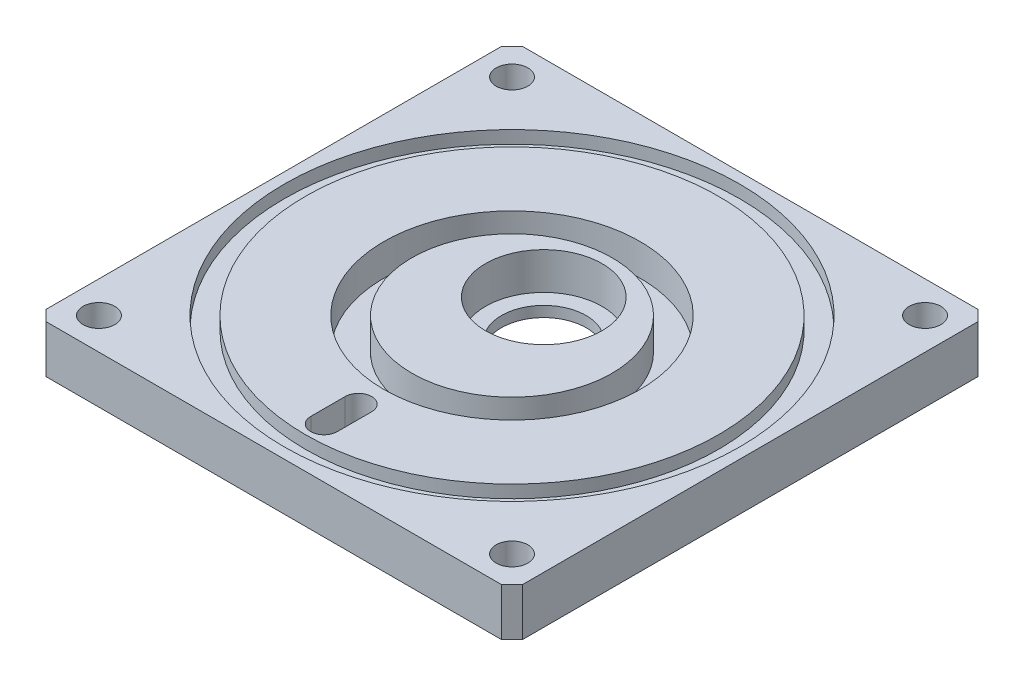
SolidWorks part; units mm, degrees
ref_plane "前视基准面" through (0, 0, 0) normal (0, 0, 1) x (1, 0, 0)
ref_plane "上视基准面" through (0, 0, 0) normal (0, 1, 0) x (1, 0, 0)
ref_plane "右视基准面" through (0, 0, 0) normal (1, 0, 0) x (0, 0, -1)
sketch "草图1" plane through (0, 0, 0) normal (0, 1, 0) x (1, 0, 0)
  line L1 (-22.5, -22.5) -> (22.5, -22.5)
  line L2 (-22.5, -22.5) -> (-22.5, 22.5)
  line L3 (-22.5, 22.5) -> (22.5, 22.5)
  line L4 (22.5, -22.5) -> (22.5, 22.5)
  line L5 (-22.5, -22.5) -> (22.5, 22.5) construction
  line L6 (-22.5, 22.5) -> (22.5, -22.5) construction
  point P0 (0, 0)
  dimension "D1" = 45
  dimension "D2" = 45
extrude "凸台-拉伸1" add sketch "草图1" along normal blind 4.5
sketch "草图2" plane through (0, 4.5, 0) normal (0, 1, 0) x (1, 0, 0)
  line L0 (0, 0) -> (0, 3) construction
  circle A0 centre (0, 3) radius 5.5
  dimension "D2" = 11
  dimension "D1" = 3
extrude "切除-拉伸1" cut sketch "草图2" against normal blind 3.5
sketch "草图3" plane through (0, 1, 0) normal (0, 1, 0) x (1, 0, 0)
  circle A0 centre (0, 3) radius 4
  dimension "D1" = 8
extrude "切除-拉伸2" cut sketch "草图3" against normal through all
sketch "草图4" plane through (0, 4.5, 0) normal (0, 1, 0) x (1, 0, 0)
  circle A0 centre (0, 0) radius 9.45
  circle A1 centre (0, 0) radius 12.1
  dimension "D1" = 18.9
  dimension "D2" = 24.2
extrude "切除-拉伸3" cut sketch "草图4" against normal blind 3
sketch "草图5" plane through (0, 4.5, 0) normal (0, 1, 0) x (1, 0, 0)
  circle A0 centre (0, 0) radius 19.5
  circle A1 centre (0, 0) radius 21.5
  dimension "D1" = 43
  dimension "D2" = 39
extrude "切除-拉伸4" cut sketch "草图5" against normal blind 1.2
sketch "草图6" plane through (0, 4.5, 0) normal (0, 1, 0) x (1, 0, 0)
  line L0 (0, -19) -> (0, -14.5) construction
  line L1 (0, -14.5) -> (0, -17.75) construction
  line L2 (1.25, -14.5) -> (1.25, -17.75)
  line L3 (-1.25, -14.5) -> (-1.25, -17.75)
  circle A0 centre (0, 0) radius 19 construction
  arc A1 (1.25, -14.5) -> (-1.25, -14.5) centre (0, -14.5) ccw
  arc A2 (-1.25, -17.75) -> (1.25, -17.75) centre (0, -17.75) ccw
  point P5 (0, -16.125)
  dimension "D1" = 38
  dimension "D2" = 4.5
  dimension "D3" = 1.25
extrude "切除-拉伸5" cut sketch "草图6" against normal through all
sketch "草图8" plane through (0, 0, 0) normal (0, -1, 0) x (1, 0, 0)
  line L0 (0, 22.5) -> (0, -22.5) construction
  line L1 (-22.5, 22.5) -> (22.5, 22.5) construction
  line L2 (22.5, -22.5) -> (-22.5, -22.5) construction
  line L3 (-22.5, 0) -> (22.5, 0) construction
  line L4 (-22.5, -22.5) -> (-22.5, 22.5) construction
  line L5 (22.5, 22.5) -> (22.5, -22.5) construction
  circle A0 centre (-19.5, 19.5) radius 1.5
  circle A1 centre (19.5, 19.5) radius 1.5
  circle A2 centre (19.5, -19.5) radius 1.5
  circle A3 centre (-19.5, -19.5) radius 1.5
  dimension "D1" = 3
  dimension "D2" = 3
  dimension "D3" = 3
extrude "切除-拉伸6" cut sketch "草图8" against normal through all
chamfer "倒角1" distance 1 angle 45 4 edges at (22.5, 2.25, -22.5) (22.5, 2.25, 22.5) (-22.5, 2.25, 22.5) (-22.5, 2.25, -22.5)
